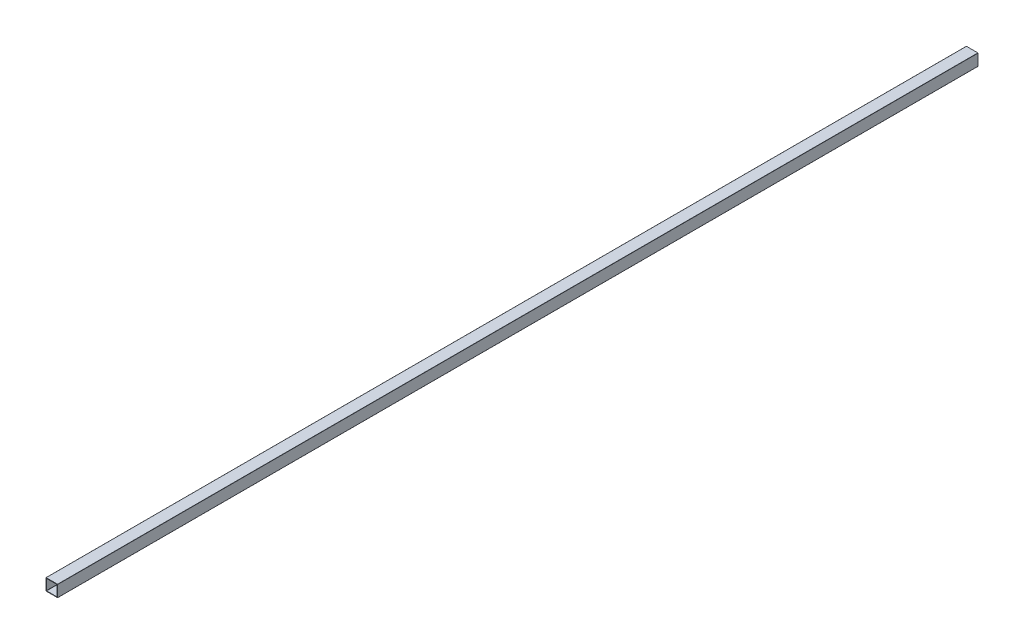
SolidWorks part; units mm, degrees
material "AISI 1035 Acero (SS)"
ref_plane "Alzado" through (0, 0, 0) normal (0, 0, 1) x (1, 0, 0)
ref_plane "Planta" through (0, 0, 0) normal (0, 1, 0) x (1, 0, 0)
ref_plane "Vista lateral" through (0, 0, 0) normal (1, 0, 0) x (0, 0, -1)
sketch "Croquis1" plane through (0, 0, 0) normal (0, 0, 1) x (1, 0, 0)
  line L0 (-35.06, -35.06) -> (-35.06, 35.06)
  line L1 (-38.1, -38.1) -> (38.1, -38.1)
  line L2 (-38.1, -38.1) -> (-38.1, 38.1)
  line L3 (-38.1, 38.1) -> (38.1, 38.1)
  line L4 (38.1, -38.1) -> (38.1, 38.1)
  line L5 (-38.1, -38.1) -> (38.1, 38.1) construction
  line L6 (-38.1, 38.1) -> (38.1, -38.1) construction
  line L7 (-35.06, 35.06) -> (35.06, 35.06)
  line L8 (35.06, -35.06) -> (35.06, 35.06)
  line L9 (-35.06, -35.06) -> (35.06, -35.06)
  point P0 (0, 0)
  dimension "D1" = 76.2
  dimension "D3" = 3.04
extrude "Saliente-Extruir1" add sketch "Croquis1" against normal blind 6000
fillet "Redondeo1" radius 1 8 edges at (-35.06, 35.06, -3000) (35.06, 35.06, -3000) (35.06, -35.06, -3000) (-38.1, -38.1, -3000) (-38.1, 38.1, -3000) (-35.06, -35.06, -3000) (38.1, -38.1, -3000) (38.1, 38.1, -3000)
